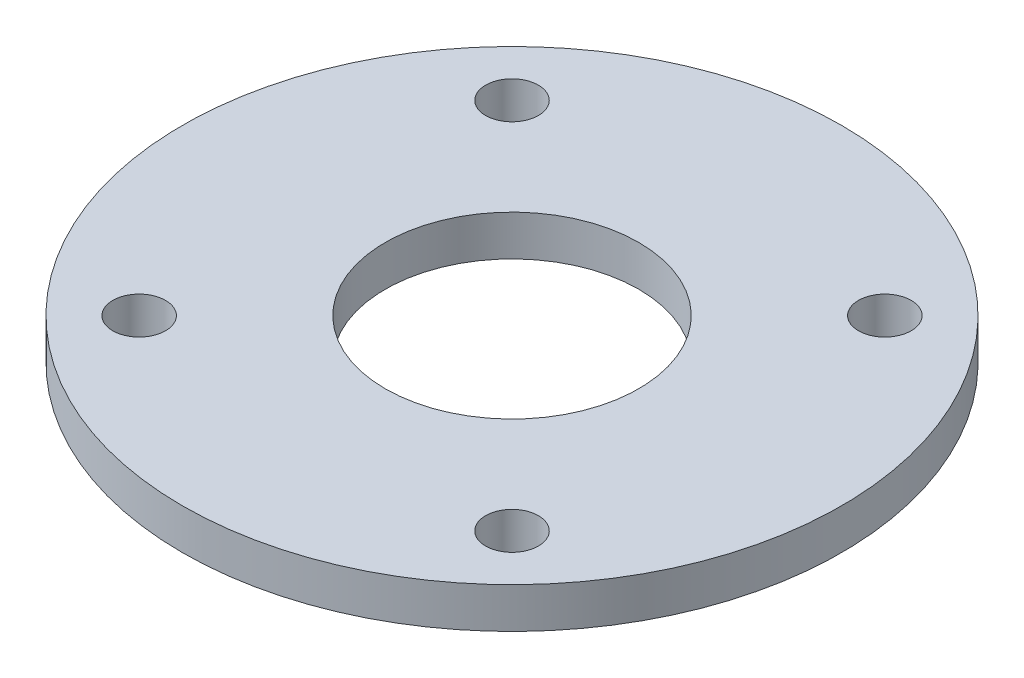
SolidWorks part; units mm, degrees
ref_plane "Front Plane" through (0, 0, 0) normal (0, 0, 1) x (1, 0, 0)
ref_plane "Top Plane" through (0, 0, 0) normal (0, 1, 0) x (1, 0, 0)
ref_plane "Right Plane" through (0, 0, 0) normal (1, 0, 0) x (0, 0, -1)
sketch "Sketch1" plane through (0, 0, 0) normal (0, 1, 0) x (1, 0, 0)
  line L1 (18.3848, -18.3848) -> (-18.3848, -18.3848) construction
  line L2 (18.3848, -18.3848) -> (18.3848, 18.3848) construction
  line L3 (18.3848, 18.3848) -> (-18.3848, 18.3848) construction
  line L4 (-18.3848, -18.3848) -> (-18.3848, 18.3848) construction
  line L5 (18.3848, -18.3848) -> (-18.3848, 18.3848) construction
  line L6 (18.3848, 18.3848) -> (-18.3848, -18.3848) construction
  circle A0 centre (0, 0) radius 12.5
  circle A1 centre (0, 0) radius 26 construction
  circle A2 centre (18.3848, -18.3848) radius 2.6
  circle A3 centre (-18.3848, -18.3848) radius 2.6
  circle A4 centre (-18.3848, 18.3848) radius 2.6
  circle A5 centre (18.3848, 18.3848) radius 2.6
  circle A6 centre (0, 0) radius 32.5
  dimension "D1" = 25
  dimension "D2" = 52
  dimension "D4" = 5.2
  dimension "D5" = 65
extrude "Boss-Extrude1" add sketch "Sketch1" along normal blind 4
